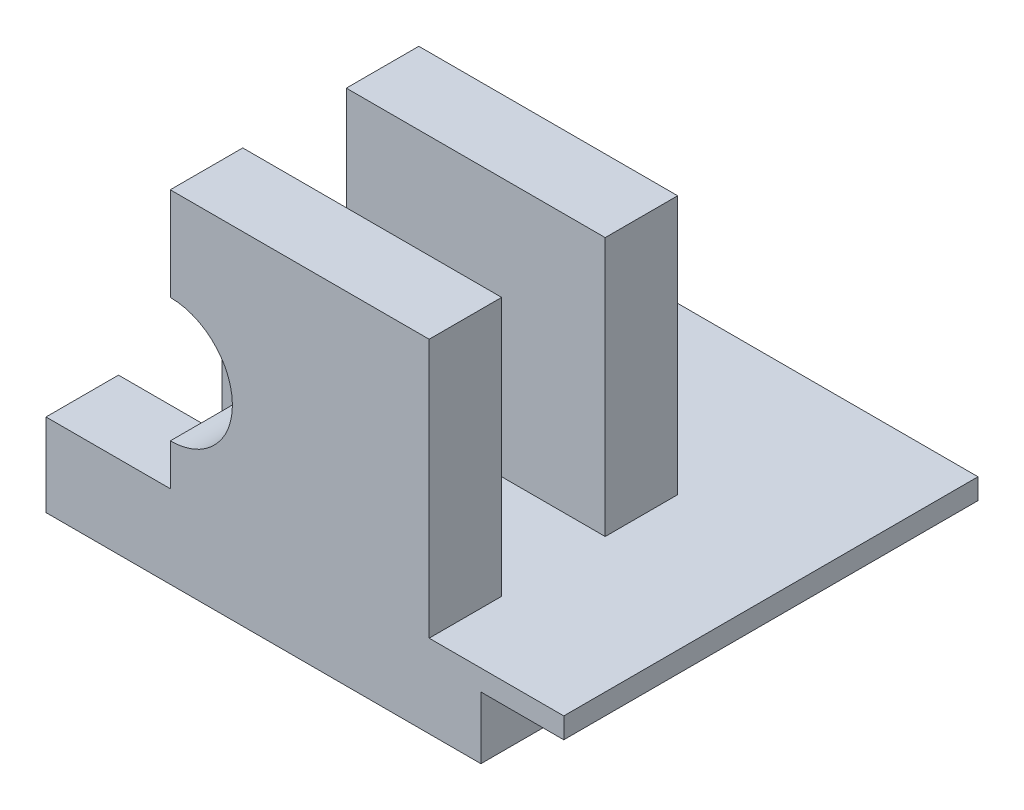
SolidWorks part; units mm, degrees
ref_plane "Спереди" through (0, 0, 0) normal (0, 0, 1) x (1, 0, 0)
ref_plane "Сверху" through (0, 0, 0) normal (0, 1, 0) x (1, 0, 0)
ref_plane "Справа" through (0, 0, 0) normal (1, 0, 0) x (0, 0, -1)
sketch "Эскиз1" plane through (0, 0, 0) normal (0, 0, 1) x (1, 0, 0)
  line L1 (-25, -4) -> (25, -4)
  line L2 (-25, -4) -> (-25, 4)
  line L3 (-25, 4) -> (25, 4)
  line L4 (25, -4) -> (25, 4)
  line L5 (-25, -4) -> (25, 4) construction
  line L6 (-25, 4) -> (25, -4) construction
  line L7 (25, -4) -> (17, -4)
  line L8 (25, -4) -> (25, 2)
  line L9 (25, 2) -> (17, 2)
  line L10 (17, -4) -> (17, 2)
  point P0 (0, 0)
  dimension "D1" = 50
  dimension "D2" = 8
  dimension "D3" = 8
  dimension "D4" = 6
extrude "Бобышка-Вытянуть1" add sketch "Эскиз1" along normal blind 40 contours L1 L10 L9 L4 L3 L2
sketch "Эскиз2" plane through (0, 4, 0) normal (0, 1, 0) x (1, 0, 0)
  line L0 (-25, 0) -> (25, 0) construction
  line L1 (-25, -40) -> (-25, 0) construction
  line L2 (-25, -40) -> (25, -40) construction
  line L3 (-25, -33) -> (-13, -33)
  line L4 (-25, -33) -> (-25, -23)
  line L5 (-25, -23) -> (-13, -23)
  line L6 (-13, -33) -> (-13, -23)
  circle A0 centre (-15, 0) radius 7.5
  dimension "D1" = 10
  dimension "D2" = 15
  dimension "D3" = 12
  dimension "D4" = 10
  dimension "D5" = 7
extrude "Вырез-Вытянуть1" cut sketch "Эскиз2" against normal through all
sketch "Эскиз3" plane through (0, 4, 0) normal (0, 1, 0) x (1, 0, 0)
  line L0 (-25, -40) -> (25, -40) construction
  line L1 (-13, -33) -> (12, -33)
  line L2 (-13, -33) -> (-13, -40)
  line L3 (-13, -40) -> (12, -40)
  line L4 (12, -33) -> (12, -40)
  line L6 (-13, -23) -> (12, -23)
  line L7 (-13, -23) -> (-13, -16)
  line L8 (-13, -16) -> (12, -16)
  line L9 (12, -23) -> (12, -16)
  dimension "D1" = 25
extrude "Бобышка-Вытянуть2" add sketch "Эскиз3" along normal blind 25
sketch "Эскиз4" plane through (0, 0, 40) normal (0, 0, 1) x (1, 0, 0)
  line L0 (-13, 29) -> (-13, 4) construction
  line L2 (-25, 4) -> (-13, 4) construction
  circle A0 centre (-13, 14) radius 6
  dimension "D1" = 12
  dimension "D2" = 10
extrude "Вырез-Вытянуть2" cut sketch "Эскиз4" against normal up to next
sketch "Эскиз6" plane through (0, 0, 23) normal (0, 0, 1) x (1, 0, 0)
  line L0 (-13, 29) -> (-13, 4) construction
  line L1 (-13, 8) -> (-5, 8)
  line L2 (-13, 8) -> (-13, 16)
  line L3 (-13, 16) -> (-5, 16)
  line L4 (-5, 8) -> (-5, 16)
  line L5 (-25, 4) -> (-13, 4) construction
  dimension "D1" = 8
  dimension "D2" = 8
  dimension "D3" = 4
extrude "Вырез-Вытянуть3" cut sketch "Эскиз6" against normal through all
